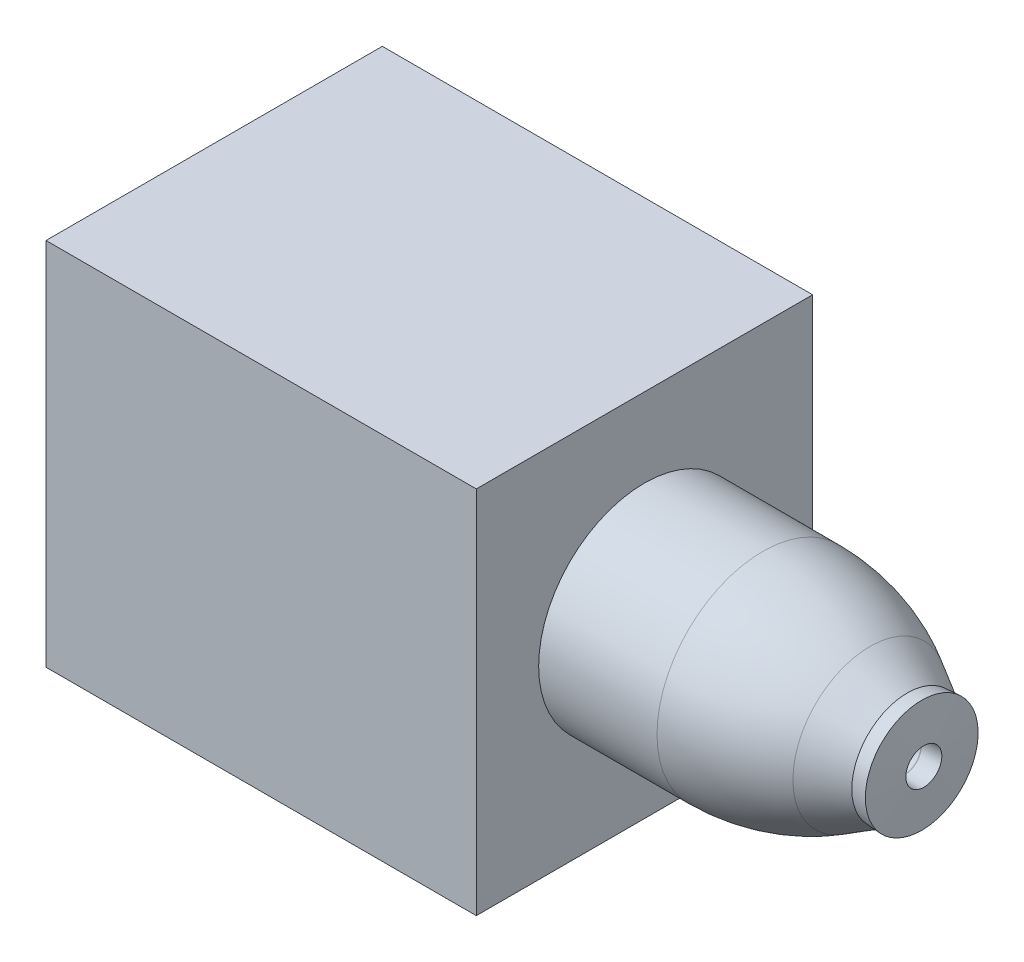
SolidWorks part; units mm, degrees
ref_plane "Front Plane" through (0, 0, 0) normal (0, 0, 1) x (1, 0, 0)
ref_plane "Top Plane" through (0, 0, 0) normal (0, 1, 0) x (1, 0, 0)
ref_plane "Right Plane" through (0, 0, 0) normal (1, 0, 0) x (0, 0, -1)
sketch "Model" plane through (0, 0, 0) normal (0, 0, 1) x (1, 0, 0)
  line L0 (0, 3.5618) -> (58.3118, 3.5618)
  line L1 (0, -3.5618) -> (58.3118, -3.5618) construction
  line L2 (62.9626, 2.3157) -> (65.1212, 1.0694)
  line L3 (62.9627, -2.3156) -> (65.1212, -1.0694) construction
  line L4 (0, 0) -> (66.8239, 0) construction
  line L5 (66.8239, 0.9515) -> (67.9239, 0.9515) construction
  line L6 (66.8239, 0.9515) -> (67.9223, 1.011) construction
  line L7 (65.8095, 0) -> (66.7, 0) construction
  line L8 (66.6984, 0.9446) -> (65.8095, 0.8911) construction
  line L9 (0, 5.5938) -> (58.3118, 5.5938)
  line L10 (63.9786, 4.0754) -> (65.9533, 2.9354)
  line L11 (0, 5.5938) -> (0, 3.5618)
  line L12 (66.7143, 2.9806) -> (66.8239, 0.9515)
  arc A0 (62.9626, 2.3157) -> (58.3118, 3.5618) centre (58.3118, -5.74) ccw
  arc A1 (58.3118, -3.5618) -> (62.9627, -2.3156) centre (58.3118, 5.74) ccw construction
  arc A2 (65.1212, 1.0694) -> (65.7891, 0.8904) centre (65.7891, 2.2261) ccw
  arc A3 (65.7891, -0.8904) -> (65.1212, -1.0694) centre (65.7891, -2.2261) ccw construction
  arc A4 (65.7891, 0.8904) -> (65.8095, 0.8911) centre (65.7891, 1.2306) ccw
  arc A5 (65.8095, -0.8911) -> (65.7891, -0.8904) centre (65.7891, -1.2306) ccw
  arc A6 (64.555, 1.715) -> (66.3002, 0.9921) centre (65.7891, 2.2262) ccw construction
  arc A7 (65.5596, 0.9795) -> (66.0402, 1.0012) centre (65.7891, 1.2306) ccw construction
  arc A8 (63.9786, 4.0754) -> (58.3118, 5.5938) centre (58.3118, -5.74) ccw
  arc A9 (65.9533, 2.9354) -> (65.9533, 2.9354) centre (65.9533, 2.9354) ccw
  arc A10 (65.9533, 2.9354) -> (65.9533, 2.9354) centre (65.9533, 2.9354) ccw
  spline S0 degree 2 poles (65.8095, 0.8911) (66.7236, 0.9461) (66.8239, 0.9515) knots 0 0 0 1 1 1
  spline S1 degree 2 poles (65.8095, -0.8911) (66.7236, -0.9461) (66.8239, -0.9515) knots 0 0 0 1 1 1 construction
  spline S2 degree 1 poles (65.9533, 2.9354) (66.7143, 2.9806) knots 0 0 1 1 construction
  spline S3 degree 2 poles (65.9533, 2.9354) (66.614, 2.9751) (66.7143, 2.9806) knots 0.156174 0.156174 0.156174 1 1 1
  text T0 "CO2 Thruster" font "SWTXT" height 5
  point P23 (66.8239, -0.9515)
  point P27 (66.8239, -0.9515)
  point P28 (66.8239, 0.9515)
  dimension "D6" = 9.3019
  dimension "D7" = 1.3357
  dimension "D11" = 0.3401
  dimension "D1" = 7.1237
  dimension "D2" = 1.7821
  dimension "D3" = 58.3118
  dimension "D4" = 65.8095
  dimension "D5" = 66.8239
  dimension "D8" = 30
  dimension "D9" = 1.9031
  dimension "D10" = 176.899
  dimension "D12" = 3.446
  dimension "D13" = 3.5618
  dimension "D14" = 2.032
revolve "Revolve1" add sketch "Model" angle 360 about L4
sketch "Sketch1" plane through (0, 0, 0) normal (0, 0, 1) x (1, 0, 0)
  line L0 (0, -9.7703) -> (0, 9.7703)
  line L2 (0, -9.7703) -> (52.0546, -9.7703)
  line L3 (0, -9.7703) -> (0, 9.7703)
  line L4 (0, 9.7703) -> (52.0546, 9.7703)
  line L5 (52.0546, -9.7703) -> (52.0546, 9.7703)
  point P4 (0, 0)
extrude "Boss-Extrude1" add sketch "Sketch1" along normal mid plane 17.78 contours L2 L5 L4 L0
sketch "Sketch3" plane through (0, 0, 8.89) normal (0, 0, 1) x (1, 0, 0)
  line L0 (0, 9.7703) -> (52.0546, 9.7703) construction
  line L1 (0, -9.7703) -> (29.304, -9.7703)
  line L2 (0, -9.7703) -> (0, 9.7703)
  line L3 (0, 9.7703) -> (29.304, 9.7703)
  line L4 (29.304, -9.7703) -> (29.304, 9.7703)
extrude "Cut-Extrude1" cut sketch "Sketch3" against normal through all
